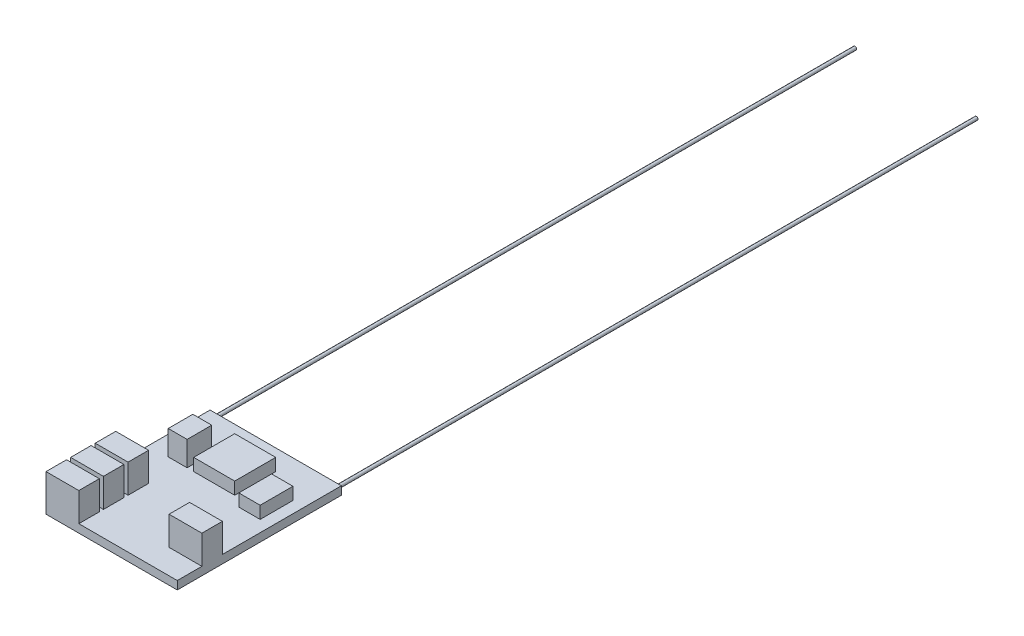
SolidWorks part; units mm, degrees
ref_plane "Front Plane" through (0, 0, 0) normal (0, 0, 1) x (1, 0, 0)
ref_plane "Top Plane" through (0, 0, 0) normal (0, 1, 0) x (1, 0, 0)
ref_plane "Right Plane" through (0, 0, 0) normal (1, 0, 0) x (0, 0, -1)
sketch "Sketch1" plane through (0, 0, 0) normal (0, 1, 0) x (1, 0, 0)
  line L1 (-8, -10) -> (8, -10)
  line L2 (-8, -10) -> (-8, 10)
  line L3 (-8, 10) -> (8, 10)
  line L4 (8, -10) -> (8, 10)
  line L5 (-8, -10) -> (8, 10) construction
  line L6 (-8, 10) -> (8, -10) construction
  point P0 (0, 0)
  dimension "D1" = 20
  dimension "D2" = 16
extrude "Boss-Extrude1" add sketch "Sketch1" along normal blind 1
sketch "Sketch2" plane through (0, 1, 0) normal (0, 1, 0) x (1, 0, 0)
  line L0 (-8, -7) -> (-8, -4.5)
  line L1 (-8, -10) -> (-4, -10)
  line L2 (-8, -10) -> (-8, -7.5)
  line L3 (-8, -7.5) -> (-4, -7.5)
  line L4 (-4, -10) -> (-4, -7.5)
  line L5 (-8, -7) -> (-4, -7)
  line L6 (-4, -7) -> (-4, -4.5)
  line L7 (-8, -4.5) -> (-4, -4.5)
  line L8 (-8, -4) -> (-8, -1.5)
  line L9 (-8, -4) -> (-4, -4)
  line L10 (-4, -4) -> (-4, -1.5)
  line L11 (-8, -1.5) -> (-4, -1.5)
  line L12 (-8, -10) -> (8, -10) construction
  line L13 (0, 0) -> (0, -10) construction
  line L14 (8, -7) -> (4, -7)
  line L15 (4, -7) -> (4, -4.5)
  line L16 (8, -4.5) -> (4, -4.5)
  line L17 (8, -7) -> (8, -4.5)
  dimension "D1" = 2.5
  dimension "D2" = 4
  dimension "D4" = 3
  dimension "D3" = 3
extrude "Boss-Extrude2" add sketch "Sketch2" along normal blind 3.5
sketch "Sketch3" plane through (0, 1, 0) normal (0, 1, 0) x (1, 0, 0)
  line L0 (0, 10) -> (0, 0) construction
  line L1 (8, 10) -> (-8, 10) construction
  line L3 (-2.5, 2.5) -> (2.5, 2.5)
  line L4 (-2.5, 2.5) -> (-2.5, 7.5)
  line L5 (-2.5, 7.5) -> (2.5, 7.5)
  line L6 (2.5, 2.5) -> (2.5, 7.5)
  line L7 (-2.5, 2.5) -> (2.5, 7.5) construction
  line L8 (-2.5, 7.5) -> (2.5, 2.5) construction
  line L9 (4, 1.5) -> (6.6, 1.5)
  line L10 (4, 1.5) -> (4, 5.5)
  line L11 (4, 5.5) -> (6.6, 5.5)
  line L12 (6.6, 1.5) -> (6.6, 5.5)
  point P5 (0, 5)
  dimension "D1" = 5
  dimension "D2" = 5
  dimension "D3" = 5
  dimension "D4" = 4
  dimension "D5" = 2.6
  dimension "D6" = 4
  dimension "D7" = 1.5
extrude "Boss-Extrude3" add sketch "Sketch3" along normal blind 1.5
sketch "Sketch4" plane through (0, 1, 0) normal (0, 1, 0) x (1, 0, 0)
  line L0 (-2.5, 2.5) -> (2.5, 2.5) construction
  line L1 (-3.3, 2.5) -> (-5.6026, 2.5)
  line L2 (-3.3, 2.5) -> (-3.3, 5.5)
  line L3 (-3.3, 5.5) -> (-5.6026, 5.5)
  line L4 (-5.6026, 2.5) -> (-5.6026, 5.5)
  dimension "D1" = 3.3
  dimension "D2" = 2.3026
  dimension "D3" = 3
extrude "Boss-Extrude4" add sketch "Sketch4" along normal blind 3
sketch "Sketch5" plane through (0, 0, -10) normal (0, 0, -1) x (-1, 0, 0)
  line L0 (0, 0) -> (0, 1) construction
  line L1 (-8, 0) -> (8, 0) construction
  line L2 (-8, 1) -> (8, 1) construction
  line L3 (8, 0.5) -> (-8, 0.5) construction
  line L4 (8, 1) -> (8, 0) construction
  line L5 (-8, 1) -> (-8, 0) construction
  circle A0 centre (7.4, 0.5) radius 0.2
  circle A1 centre (-7.4, 0.5) radius 0.2
  dimension "D1" = 0.4
  dimension "D2" = 0.6
extrude "Boss-Extrude5" add sketch "Sketch5" along normal blind 78
